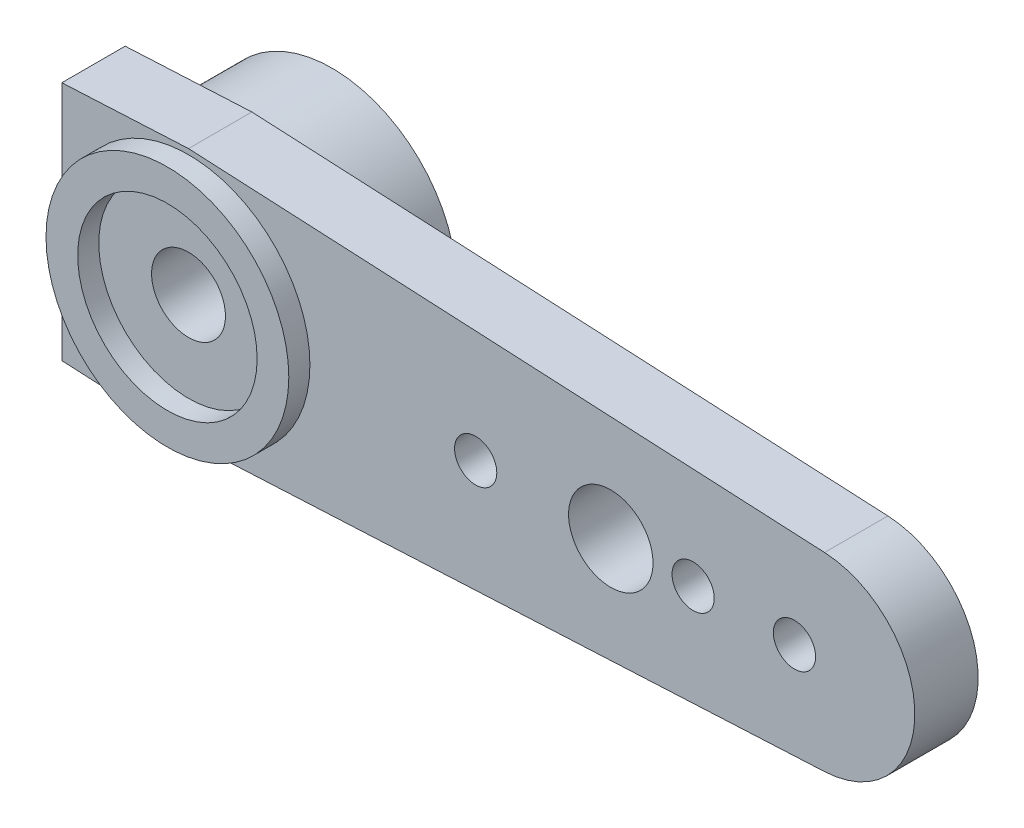
SolidWorks part; units mm, degrees
ref_plane "Front" through (0, 0, 0) normal (0, 0, 1) x (1, 0, 0)
ref_plane "Top" through (0, 0, 0) normal (0, 1, 0) x (1, 0, 0)
ref_plane "Right" through (0, 0, 0) normal (1, 0, 0) x (0, 0, -1)
sketch "Sketch1" plane through (0, 0, 0) normal (0, 0, 1) x (1, 0, 0)
  circle A0 centre (0, 0) radius 2.25
  circle A1 centre (0, 0) radius 2.95
  dimension "D1" = 5.9
  dimension "D2" = 0.7
extrude "Boss-Extrude1" add sketch "Sketch1" along normal blind 1.9
sketch "Sketch2" plane through (0, 0, 1.9) normal (0, 0, 1) x (1, 0, 0)
  line L0 (0, 0) -> (0, 2.95) construction
  line L1 (15.0623, 2.2472) -> (0, 3)
  line L2 (0, 0) -> (14.95, 0) construction
  line L3 (-15.0623, 2.2472) -> (0, 3)
  line L4 (-15.0623, -2.2472) -> (0, -3)
  line L5 (15.0623, -2.2472) -> (0, -3)
  arc A0 (-15.0623, -2.2472) -> (-15.0623, 2.2472) centre (-14.95, 0) cw
  arc A1 (15.0623, -2.2472) -> (15.0623, 2.2472) centre (14.95, 0) ccw
  circle A2 centre (0, 0) radius 2.95 construction
  circle A3 centre (0, 0) radius 0.875
  circle A4 centre (6.8, 0) radius 0.5
  circle A5 centre (9.55, 0) radius 0.5
  circle A6 centre (11.95, 0) radius 0.5
  circle A7 centre (14.35, 0) radius 0.5
  circle A8 centre (-14.35, 0) radius 0.5
  circle A9 centre (-11.95, 0) radius 0.5
  circle A10 centre (-9.55, 0) radius 0.5
  circle A11 centre (-6.8, 0) radius 0.5
  dimension "D1" = 3
  dimension "D2" = 2.25
  dimension "D3" = 29.9
  dimension "D4" = 1.75
  dimension "D5" = 1
  dimension "D6" = 2.75
  dimension "D7" = 2.4
  dimension "D8" = 2.4
  dimension "D9" = 13.6
extrude "Boss-Extrude2" add sketch "Sketch2" along normal blind 1.5
sketch "Sketch3" plane through (0, 0, 3.4) normal (0, 0, 1) x (1, 0, 0)
  circle A0 centre (0, 0) radius 2.875
  circle A1 centre (0, 0) radius 2.125
  dimension "D1" = 5.75
  dimension "D2" = 0.75
extrude "Boss-Extrude3" add sketch "Sketch3" along normal blind 0.5
sketch "Sketch4" plane through (0, 0, 3.4) normal (0, 0, 1) x (1, 0, 0)
  circle A0 centre (10, 0) radius 1
  dimension "D2" = 2
  dimension "D1" = 10
extrude "Cut-Extrude1" cut sketch "Sketch4" against normal through all
sketch "Sketch5" plane through (0, 0, 3.4) normal (0, 0, 1) x (1, 0, 0)
  line L0 (-3, 2.8501) -> (-3, -2.8501)
  line L1 (0, 3) -> (-15.0623, 2.2472) construction
  line L2 (-15.0623, -2.2472) -> (0, -3) construction
  line L3 (-15.0623, -2.2472) -> (-3, -2.8501)
  line L4 (-3, 2.8501) -> (-15.0623, 2.2472)
  circle A0 centre (0, 0) radius 2.875 construction
  arc A1 (-15.0623, 2.2472) -> (-15.0623, -2.2472) centre (-14.95, 0) ccw construction
  arc A2 (-15.0623, 2.2472) -> (-15.0623, -2.2472) centre (-14.95, 0) ccw
  dimension "D1" = 3
extrude "Cut-Extrude2" cut sketch "Sketch5" against normal through all
